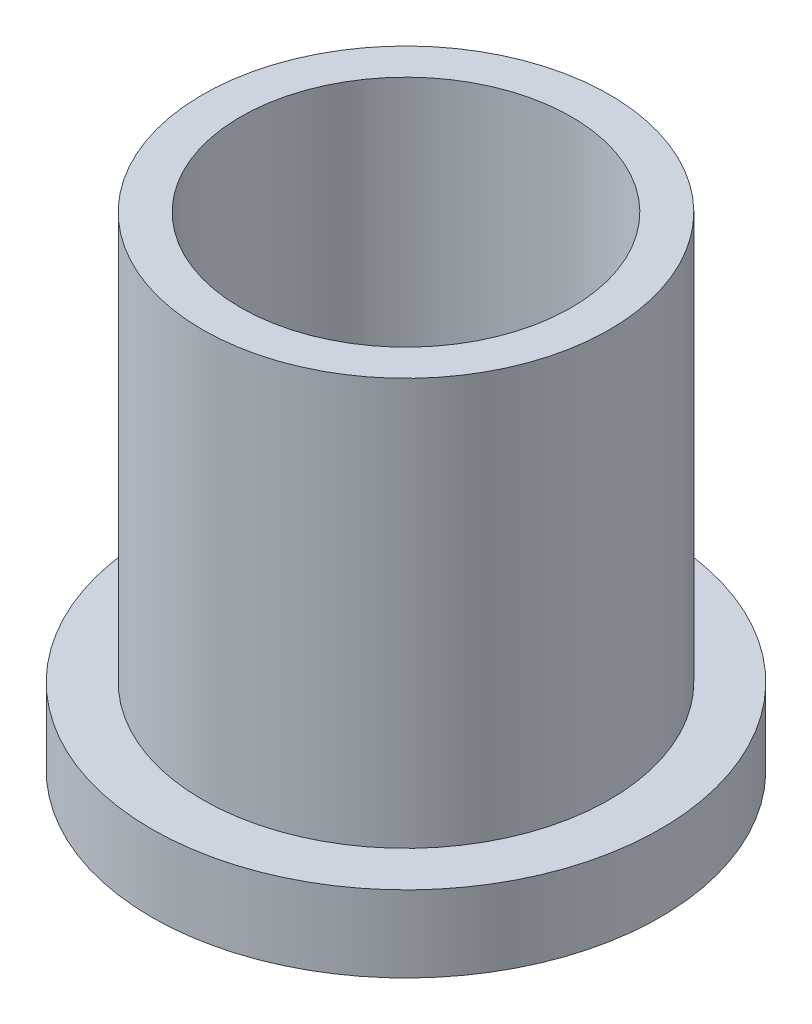
SolidWorks part; units mm, degrees
ref_plane "Спереди" through (0, 0, 0) normal (0, 0, 1) x (1, 0, 0)
ref_plane "Сверху" through (0, 0, 0) normal (0, 1, 0) x (1, 0, 0)
ref_plane "Справа" through (0, 0, 0) normal (1, 0, 0) x (0, 0, -1)
sketch "Эскиз1" plane through (0, 0, 0) normal (0, 1, 0) x (1, 0, 0)
  circle A0 centre (0, 0) radius 10
  circle A1 centre (0, 0) radius 6.5
  dimension "D1" = 20
  dimension "D2" = 13
extrude "Бобышка-Вытянуть1" add sketch "Эскиз1" along normal blind 3
sketch "Эскиз2" plane through (0, 3, 0) normal (0, 1, 0) x (1, 0, 0)
  circle A0 centre (0, 0) radius 6.5
  circle A1 centre (0, 0) radius 8
  dimension "D1" = 16
extrude "Бобышка-Вытянуть2" add sketch "Эскиз2" along normal blind 16
